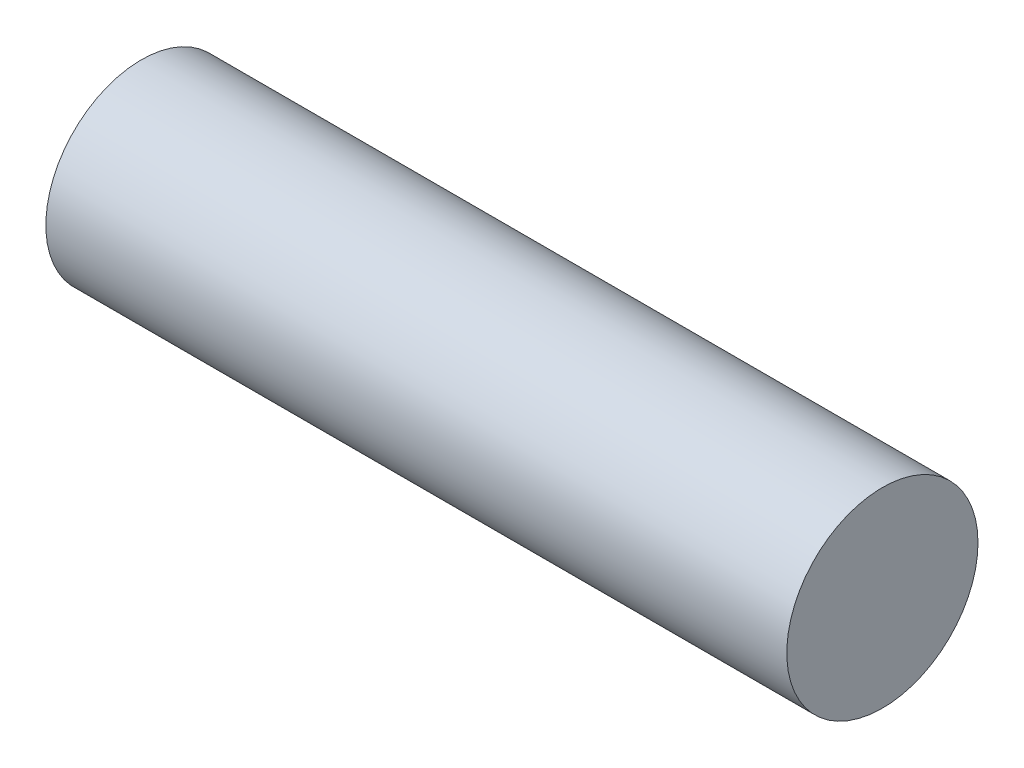
SolidWorks part; units mm, degrees
ref_plane "Front Plane" through (0, 0, 0) normal (1, 0, 0) x (0, 1, 0)
ref_plane "Top Plane" through (0, 0, 0) normal (0, 0, 1) x (0, 1, 0)
ref_plane "Right Plane" through (0, 0, 0) normal (0, 1, 0) x (-1, 0, 0)
sketch "Sketch1" plane through (0, 0, 0) normal (1, 0, 0) x (0, 1, 0)
  circle A0 centre (0, 0) radius 4
  circle A1 centre (0, 0) radius 3
  dimension "D1" = 6
  dimension "D2" = 8
extrude "Boss-Extrude1" add sketch "Sketch1" along normal blind 30
sketch "Sketch3" plane through (30, 0, 0) normal (1, 0, 0) x (0, 1, 0)
  circle A0 centre (0, 0) radius 4 construction
  circle A1 centre (0, 0) radius 4
extrude "Boss-Extrude2" add sketch "Sketch3" along normal blind 1
